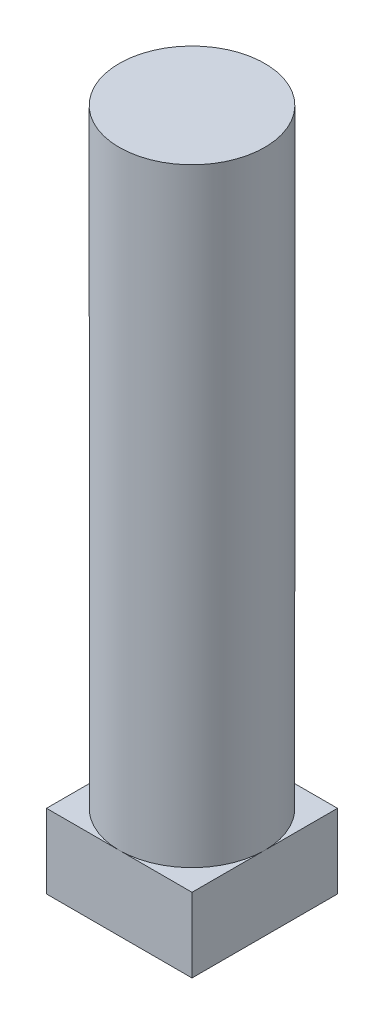
SolidWorks part; units mm, degrees
ref_plane "Front Plane" through (0, 0, 0) normal (0, 0, 1) x (1, 0, 0)
ref_plane "Top Plane" through (0, 0, 0) normal (0, 1, 0) x (1, 0, 0)
ref_plane "Right Plane" through (0, 0, 0) normal (1, 0, 0) x (0, 0, -1)
sketch "Sketch1" plane through (0, 0, 0) normal (0, 1, 0) x (1, 0, 0)
  line L1 (-2.45, -2.45) -> (2.45, -2.45)
  line L2 (-2.45, -2.45) -> (-2.45, 2.45)
  line L3 (-2.45, 2.45) -> (2.45, 2.45)
  line L4 (2.45, -2.45) -> (2.45, 2.45)
  line L5 (-2.45, -2.45) -> (2.45, 2.45) construction
  line L6 (-2.45, 2.45) -> (2.45, -2.45) construction
  point P0 (0, 0)
  dimension "D1" = 4.9
extrude "Boss-Extrude1" add sketch "Sketch1" along normal blind 2.5 contours L2 L3 L4 L1
sketch "Sketch2" plane through (0, 2.5, 0) normal (0, 1, 0) x (1, 0, 0)
  line L0 (2.45, -2.45) -> (2.45, 2.45) construction
  circle A0 centre (0, 0) radius 2.45
extrude "Boss-Extrude2" add sketch "Sketch2" along normal blind 20.5
equation "\"a\"= 1"
equation "\"b\"= 1"
equation "\"c\"= 1"
equation "\"d\"= 1"
equation "\"e\"= 1"
equation "\"x\"= 1"
equation "\"y\"= 1"
equation "\"z\"= 1"
